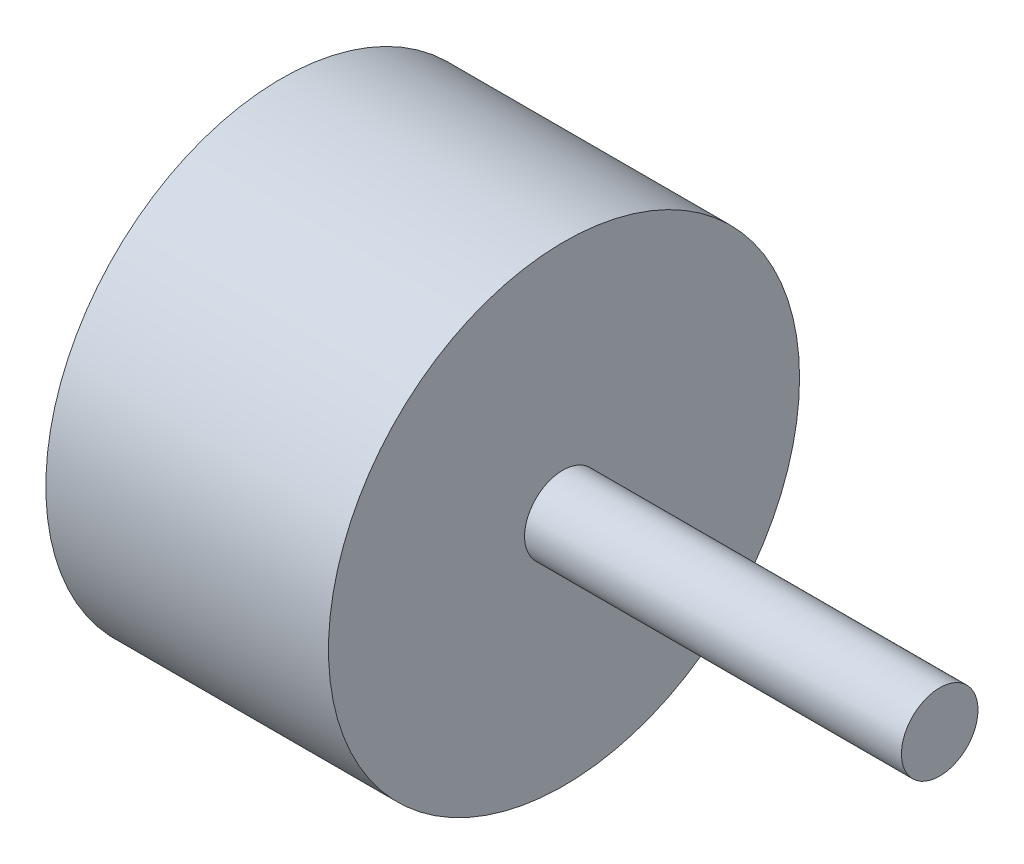
SolidWorks part; units mm, degrees
ref_plane "Front Plane" through (0, 0, 0) normal (0, 0, 1) x (1, 0, 0)
ref_plane "Top Plane" through (0, 0, 0) normal (0, 1, 0) x (1, 0, 0)
ref_plane "Right Plane" through (0, 0, 0) normal (1, 0, 0) x (0, 0, -1)
sketch "Sketch1" plane through (0, 0, 0) normal (1, 0, 0) x (0, 0, -1)
  circle A0 centre (1.2281, 0) radius 250
  dimension "D1" = 500
extrude "Boss-Extrude1" add sketch "Sketch1" along normal blind 300
sketch "Sketch2" plane through (300, 0, 0) normal (1, 0, 0) x (0, 0, -1)
  circle A0 centre (0, 0) radius 40.6261
extrude "Boss-Extrude3" add sketch "Sketch2" along normal blind 400
